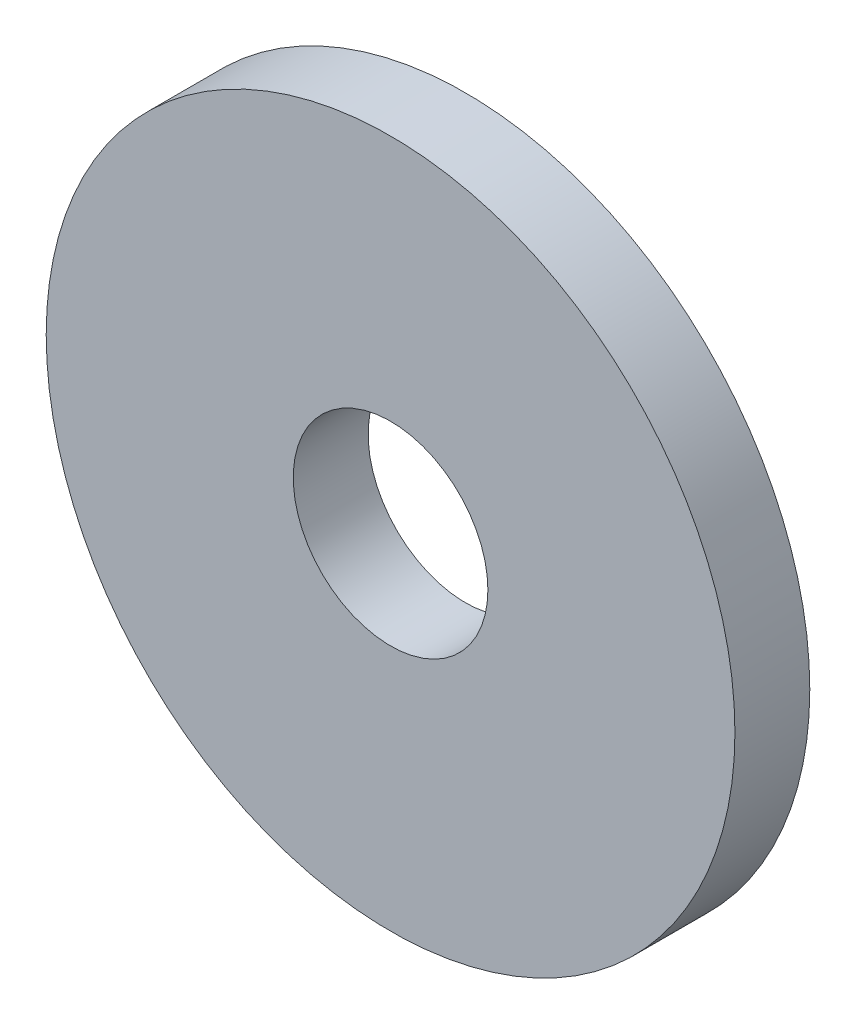
SolidWorks part; units mm, degrees
ref_plane "Front Plane" through (0, 0, 0) normal (0, 0, 1) x (1, 0, 0)
ref_plane "Top Plane" through (0, 0, 0) normal (0, 1, 0) x (1, 0, 0)
ref_plane "Right Plane" through (0, 0, 0) normal (1, 0, 0) x (0, 0, -1)
sketch "Sketch1" plane through (0, 0, 0) normal (0, 0, 1) x (1, 0, 0)
  circle A0 centre (0, 0) radius 23
  circle A1 centre (0, 0) radius 6.5
extrude "Boss-Extrude1" add sketch "Sketch1" along normal blind 5
